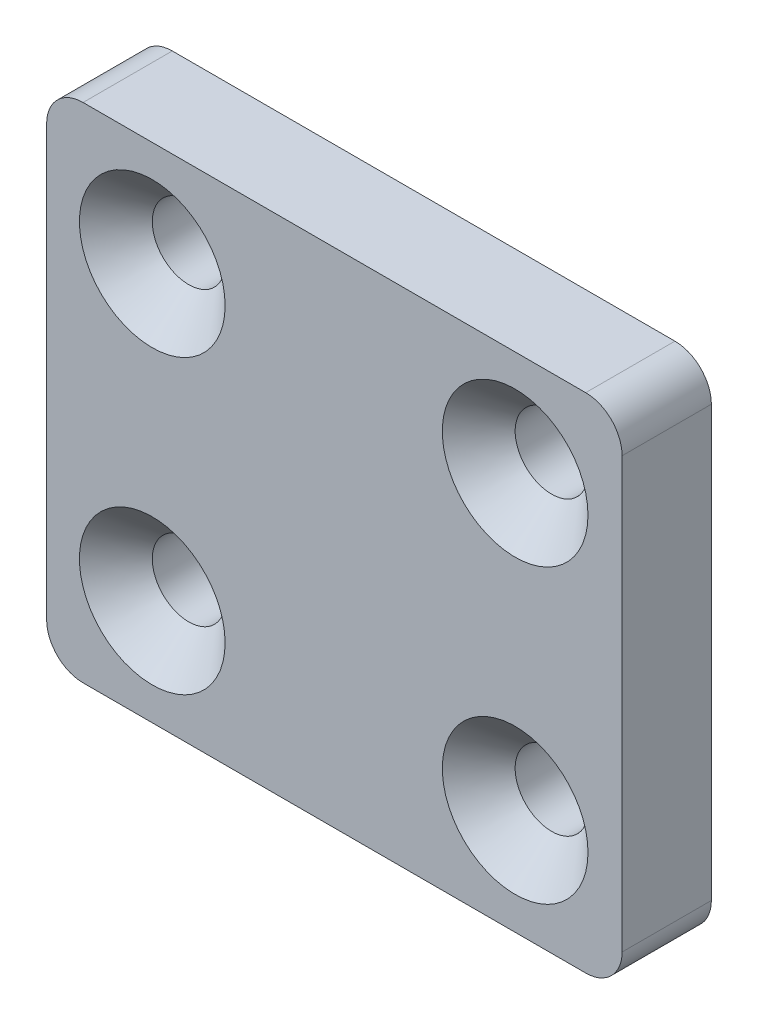
SolidWorks part; units mm, degrees
ref_plane "前视基准面" through (0, 0, 0) normal (0, 0, 1) x (1, 0, 0)
ref_plane "上视基准面" through (0, 0, 0) normal (0, 1, 0) x (1, 0, 0)
ref_plane "右视基准面" through (0, 0, 0) normal (1, 0, 0) x (0, 0, -1)
sketch "草图1" plane through (0, 0, 0) normal (0, 0, 1) x (1, 0, 0)
  line L1 (-6.9, 6.9) -> (6.9, 6.9)
  line L2 (-7.9, 5.9) -> (-7.9, -5.9)
  line L3 (-6.9, -6.9) -> (6.9, -6.9)
  line L4 (7.9, 5.9) -> (7.9, -5.9)
  line L5 (-7.9, 6.9) -> (7.9, -6.9) construction
  line L6 (-7.9, -6.9) -> (7.9, 6.9) construction
  arc A0 (-7.9, -5.9) -> (-6.9, -6.9) centre (-6.9, -5.9) ccw
  arc A1 (6.9, -6.9) -> (7.9, -5.9) centre (6.9, -5.9) ccw
  arc A2 (6.9, 6.9) -> (7.9, 5.9) centre (6.9, 5.9) cw
  arc A3 (-6.9, 6.9) -> (-7.9, 5.9) centre (-6.9, 5.9) ccw
  point P0 (0, 0)
  dimension "D3" = 1
  dimension "D1" = 13.8
  dimension "D2" = 15.8
extrude "凸台-拉伸1" add sketch "草图1" along normal blind 2.45
ref_plane "基准面4" through (0, 0, 0) normal (1, 0, 0) x (0, 0, -1)
sketch "草图3" plane through (0, 0, 0) normal (1, 0, 0) x (0, 0, -1)
  line L9 (-0.375, 6.9) -> (-0.375, -6.9) construction
  line L10 (-2.45, 6.9) -> (0, 6.9) construction
  line L11 (-2.45, -6.9) -> (0, -6.9) construction
  line L12 (0, -5.9) -> (0, 5.9) construction
  line L20 (0.0087, -0.7283) -> (0.0087, 0.7717)
  line L21 (0.0087, -6.7283) -> (0.0087, -5.2283)
  line L22 (0.0087, -4.7283) -> (0.0087, -3.2283)
  line L23 (0.0087, -2.7283) -> (0.0087, -1.2283)
  line L24 (0.0087, 1.2717) -> (0.0087, 2.7717)
  line L25 (0.0087, 3.2717) -> (0.0087, 4.7717)
  line L26 (0.0087, 5.2717) -> (0.0087, 6.7717)
  arc A14 (0.0087, 0.7717) -> (0.0087, -0.7283) centre (0.0087, 0.0217) ccw
  arc A15 (0.0087, -5.2283) -> (0.0087, -6.7283) centre (0.0087, -5.9783) ccw
  arc A16 (0.0087, -3.2283) -> (0.0087, -4.7283) centre (0.0087, -3.9783) ccw
  arc A17 (0.0087, -1.2283) -> (0.0087, -2.7283) centre (0.0087, -1.9783) ccw
  arc A18 (0.0087, 2.7717) -> (0.0087, 1.2717) centre (0.0087, 2.0217) ccw
  arc A19 (0.0087, 4.7717) -> (0.0087, 3.2717) centre (0.0087, 4.0217) ccw
  arc A20 (0.0087, 6.7717) -> (0.0087, 5.2717) centre (0.0087, 6.0217) ccw
  dimension "D1" = 0.375
extrude "切除-拉伸1" cut sketch "草图3" against normal blind 3.1 and the other way blind 3.1
sketch "草图4" plane through (0, 0, 2.45) normal (0, 0, 1) x (1, 0, 0)
  line L0 (0, 6.9) -> (0, -6.9) construction
  line L1 (6.9, 6.9) -> (-6.9, 6.9) construction
  line L2 (-6.9, -6.9) -> (6.9, -6.9) construction
  line L3 (-0.0184, 7.0092) -> (-0.0184, -6.9908) construction
  line L4 (-7.9, 5.9) -> (-7.9, -5.9) construction
  line L5 (-7.9, 0) -> (7.9, 0) construction
  line L6 (7.9, -5.9) -> (7.9, 5.9) construction
  line L7 (-6.5184, 0.0092) -> (6.4816, 0.0092) construction
  line L8 (-6.725, -2) -> (-3.275, -2) construction
  line L9 (-5, -2) -> (-5, -6) construction
  circle A0 centre (-5, -4) radius 1
  circle A1 centre (4.9632, -4) radius 1
  circle A2 centre (4.9632, 4.0184) radius 1
  circle A3 centre (-5, 4.0184) radius 1
  point P22 (-5, -4)
  dimension "D2" = 2
  dimension "D1" = 5
  dimension "D3" = 4
extrude "切除-拉伸2" cut sketch "草图4" against normal blind 6.1
chamfer "倒角1" distance 1 angle 45 4 edges at (-4, -4, 2.45) (3.9632, -4, 2.45) (5.9632, 4.0184, 2.45) (-6, 4.0184, 2.45)
